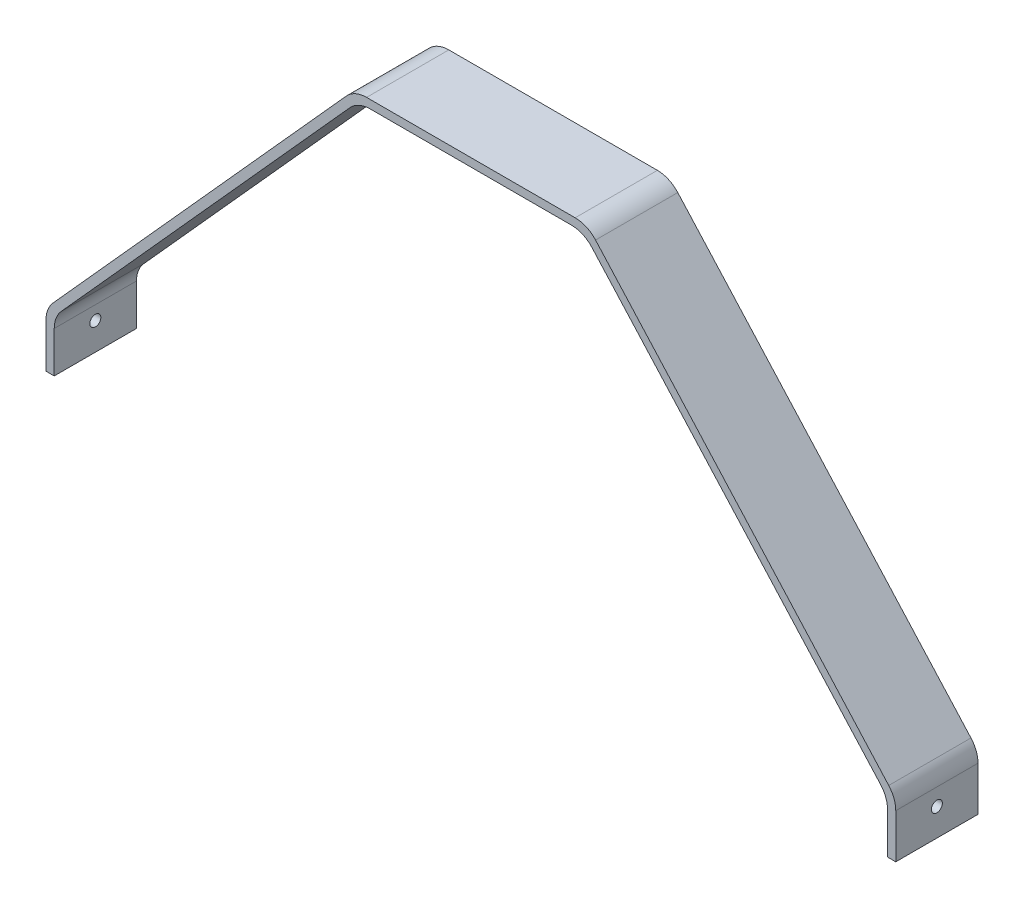
SolidWorks part; units mm, degrees
ref_plane "Front Plane" through (0, 0, 0) normal (0, 0, 1) x (1, 0, 0)
ref_plane "Top Plane" through (0, 0, 0) normal (0, 1, 0) x (1, 0, 0)
ref_plane "Right Plane" through (0, 0, 0) normal (1, 0, 0) x (0, 0, -1)
sketch "Sketch1" plane through (0, 0, 0) normal (0, 0, 1) x (1, 0, 0)
  line L0 (-42.5, 0) -> (42.5, 0)
  line L5 (0, 0) -> (0, -145) construction
  line L6 (42.5, 0) -> (155, -125)
  line L7 (-155, -145) -> (155, -145) construction
  line L8 (155, -145) -> (155, -125)
  line L9 (-155, -145) -> (-155, -125)
  line L10 (-42.5, 0) -> (-155, -125)
  line L11 (-152, -145) -> (-152, -126.1512)
  line L12 (-41.1639, -3) -> (-152, -126.1512)
  line L13 (-41.1639, -3) -> (41.1639, -3)
  line L14 (41.1639, -3) -> (152, -126.1512)
  line L15 (152, -145) -> (152, -126.1512)
  line L16 (-155, -145) -> (-152, -145)
  line L17 (155, -145) -> (152, -145)
  line L18 (152, -145) -> (155, -145)
  line L19 (-155, -145) -> (-152, -145)
  point P3 (0, 0)
  point P13 (0, -145)
  dimension "D1" = 85
  dimension "D2" = 145
  dimension "D3" = 310
  dimension "D4" = 20
  dimension "D5" = 3
extrude "Boss-Extrude1" add sketch "Sketch1" along normal blind 30 contours L17 L8 L6 L0 L10 L9 L16 L11 L12 L13 L14 L15
sketch "Sketch2" plane through (155, 0, 0) normal (1, 0, 0) x (0, 0, -1)
  line L0 (-30, -125) -> (0, -145) construction
  circle A0 centre (-15, -135) radius 2
  dimension "D1" = 4
fillet "Fillet1" radius 10 8 edges at (-152, -126.1512, 15) (-41.1639, -3, 15) (152, -126.1512, 15) (41.1639, -3, 15) (-155, -125, 15) (-42.5, 0, 15) (42.5, 0, 15) (155, -125, 15)
extrude "Cut-Extrude1" cut sketch "Sketch2" against normal through all both
